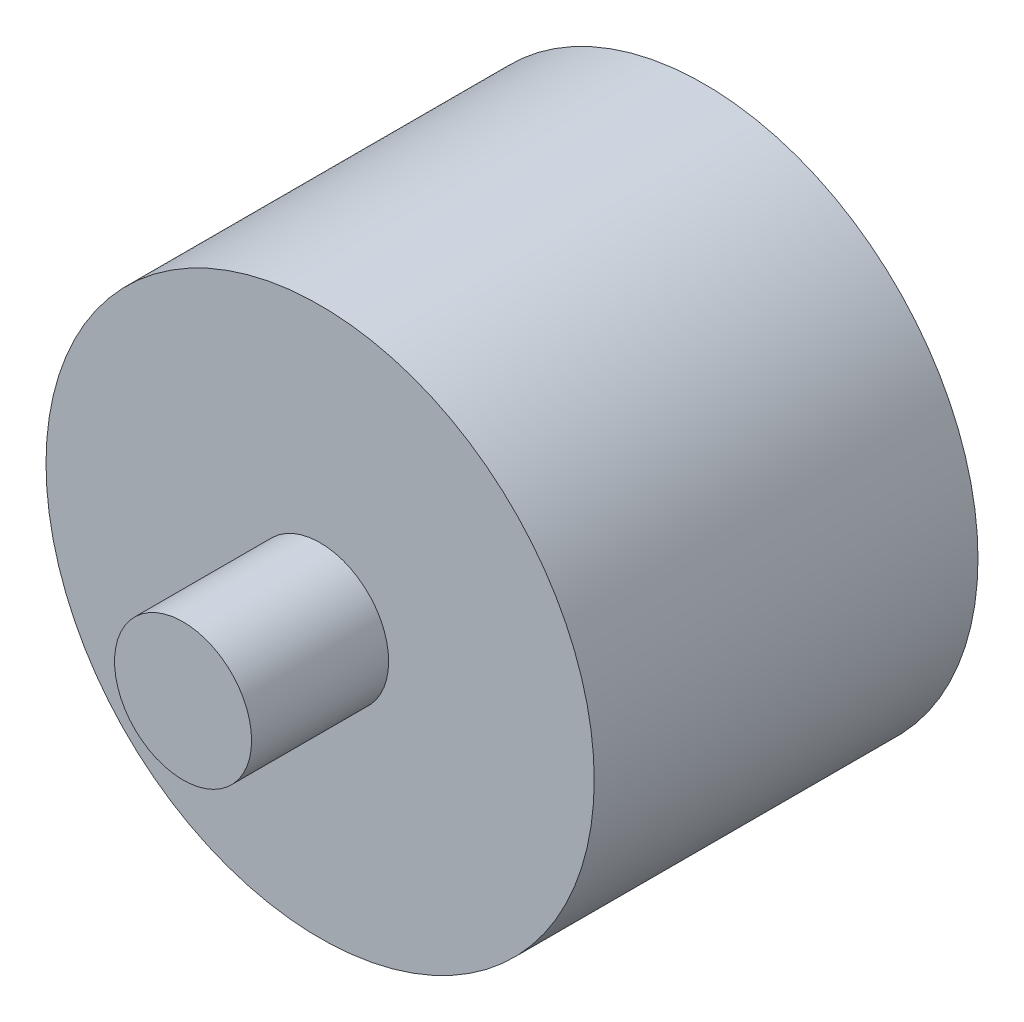
SolidWorks part; units mm, degrees
ref_plane "Front Plane" through (0, 0, 0) normal (0, 0, 1) x (1, 0, 0)
ref_plane "Top Plane" through (0, 0, 0) normal (0, 1, 0) x (1, 0, 0)
ref_plane "Right Plane" through (0, 0, 0) normal (1, 0, 0) x (0, 0, -1)
sketch "Sketch1" plane through (0, 0, 0) normal (0, 0, 1) x (1, 0, 0)
  circle A0 centre (0, 0) radius 2.5
  dimension "D1" = 5
extrude "Boss-Extrude1" add sketch "Sketch1" along normal blind 24
sketch "Sketch2" plane through (0, 0, 24) normal (0, 0, 1) x (1, 0, 0)
  circle A0 centre (0, 0) radius 10
  dimension "D1" = 20
extrude "Boss-Extrude2" add sketch "Sketch2" against normal offset from surface (14 mm away) 5 from offset 5 up to face at (2.5, 0, 0)
